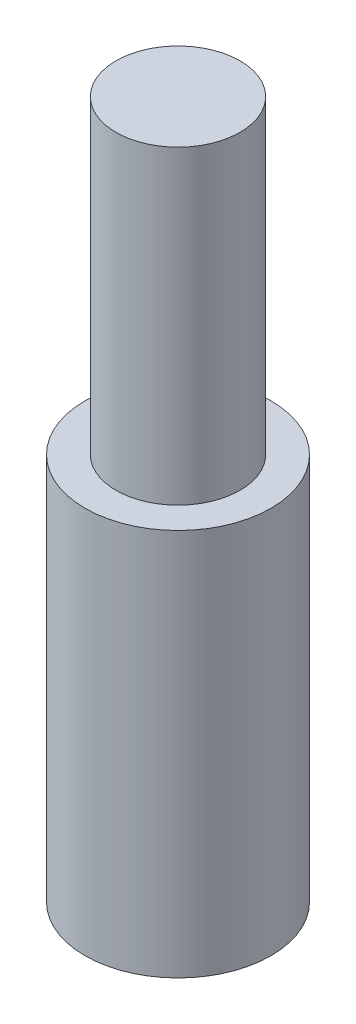
SolidWorks part; units mm, degrees
ref_plane "Ebene vorne" through (0, 0, 0) normal (0, 0, 1) x (1, 0, 0)
ref_plane "Ebene oben" through (0, 0, 0) normal (0, 1, 0) x (1, 0, 0)
ref_plane "Ebene rechts" through (0, 0, 0) normal (1, 0, 0) x (0, 0, -1)
sketch "Skizze1" plane through (0, 0, 0) normal (0, 0, 1) x (1, 0, 0)
  line L0 (0, 45) -> (0, 0)
  line L3 (0, 45) -> (4, 45)
  line L4 (4, 45) -> (4, 25)
  line L5 (4, 25) -> (6, 25)
  line L6 (6, 25) -> (6, 0)
  line L7 (6, 0) -> (0, 0)
  line L8 (0, -3.346) -> (0, 54.7199) construction
  dimension "D1" = 6
  dimension "D2" = 20
  dimension "D3" = 25
  dimension "D4" = 4
revolve "Rotation3" add sketch "Skizze1" angle 360 about L8
